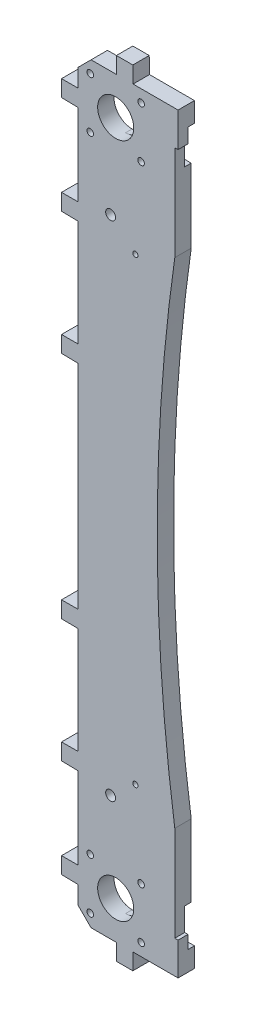
SolidWorks part; units mm, degrees
ref_plane "Front" through (0, 0, 0) normal (0, 0, 1) x (1, 0, 0)
ref_plane "Top" through (0, 0, 0) normal (0, 1, 0) x (1, 0, 0)
ref_plane "Right" through (0, 0, 0) normal (1, 0, 0) x (0, 0, -1)
sketch "Эскиз2" plane through (0, 0, 0) normal (0, 0, 1) x (1, 0, 0)
  line L0 (-25.5007, 139.9) -> (-25.5007, 109.05)
  line L1 (-35.4993, 140.0666) -> (-25.5007, 139.9)
  line L2 (-35.4993, 150.0666) -> (-35.4993, 140.0666)
  line L3 (-25.5007, 150.1) -> (-35.4993, 150.0666)
  line L4 (-25.5007, 176.55) -> (-25.5007, 150.1)
  line L5 (-25.5007, 199.9) -> (-25.5007, 176.55)
  line L6 (-35.4993, 200.0666) -> (-25.5007, 199.9)
  line L7 (-35.4993, 210.0666) -> (-35.4993, 200.0666)
  line L8 (-25.5007, 210.1) -> (-35.4993, 210.0666)
  line L9 (-25.5007, 221) -> (-25.5007, 210.1)
  line L10 (-17.5007, 229) -> (-25.5007, 221)
  line L11 (-2.1007, 229) -> (-17.5007, 229)
  line L12 (-2.0673, 238.9986) -> (-2.1007, 229)
  line L13 (7.9327, 238.9986) -> (-2.0673, 238.9986)
  line L14 (8.0993, 229) -> (7.9327, 238.9986)
  line L15 (35.4993, 229) -> (8.0993, 229)
  line L16 (8.0993, -229) -> (35.4993, -229)
  line L17 (7.9327, -238.9986) -> (8.0993, -229)
  line L18 (-2.0673, -238.9986) -> (7.9327, -238.9986)
  line L19 (-2.1007, -229) -> (-2.0673, -238.9986)
  line L20 (-17.5007, -229) -> (-2.1007, -229)
  line L21 (-25.5007, -221) -> (-17.5007, -229)
  line L22 (-25.5007, -210.1) -> (-25.5007, -221)
  line L23 (-35.4993, -209.9334) -> (-25.5007, -210.1)
  line L24 (-35.4993, -199.9334) -> (-35.4993, -209.9334)
  line L25 (-25.5007, -199.9) -> (-35.4993, -199.9334)
  line L26 (-25.5007, -173.45) -> (-25.5007, -199.9)
  line L27 (-25.5007, -150.1) -> (-25.5007, -173.45)
  line L28 (-35.4993, -149.9334) -> (-25.5007, -150.1)
  line L29 (-35.4993, -139.9334) -> (-35.4993, -149.9334)
  line L30 (-25.5007, -139.9) -> (-35.4993, -139.9334)
  line L31 (-25.5007, -105.95) -> (-25.5007, -139.9)
  line L32 (-25.5007, -75.1) -> (-25.5007, -105.95)
  line L33 (-35.4993, -74.9334) -> (-25.5007, -75.1)
  line L34 (-35.4993, -64.9334) -> (-35.4993, -74.9334)
  line L35 (-25.5007, -64.9) -> (-35.4993, -64.9334)
  line L36 (-25.5007, 64.9) -> (-25.5007, -64.9)
  line L37 (-35.4993, 65.0666) -> (-25.5007, 64.9)
  line L38 (-35.4993, 75.0666) -> (-35.4993, 65.0666)
  line L39 (-25.5007, 75.1) -> (-35.4993, 75.0666)
  line L40 (-25.5007, 109.05) -> (-25.5007, 75.1)
  line L41 (33.4993, 208.1167) -> (33.4993, 150.1167)
  line L42 (33.4993, -209) -> (33.4993, -151)
  line L43 (35.4993, -229) -> (35.4993, -209)
  line L44 (35.4993, -209) -> (33.4993, -209)
  line L45 (35.4993, 229) -> (35.4993, 208.1167)
  line L46 (35.4993, 208.1167) -> (33.4993, 208.1167)
  circle A0 centre (-18.0007, -190.5) radius 2
  circle A1 centre (-18.0007, -221.5) radius 2
  circle A2 centre (-18.0007, 190.5) radius 2
  circle A3 centre (12.9993, 221.5) radius 2
  circle A4 centre (-2.5007, -206) radius 11
  circle A5 centre (-2.5007, 206) radius 11
  circle A6 centre (-18.0007, 221.5) radius 2
  circle A7 centre (12.9993, -221.5) radius 2
  circle A8 centre (12.9993, -190.5) radius 2
  circle A9 centre (12.9993, 190.5) radius 2
  arc A12 (33.4993, 150.1167) -> (33.4993, -151) centre (1086.4428, -0.4417) ccw
  circle A15 centre (-5.6007, -153.2) radius 3
  circle A16 centre (-5.6007, 153.2) radius 3
  circle A17 centre (9.4993, -139.9) radius 1.6
  circle A18 centre (9.4993, 139.9) radius 1.6
  point P27 (0, 0)
  dimension "D1" = 58
  dimension "D2" = 58
  dimension "D3" = 2
extrude "Бобышка-Вытянуть1" add sketch "Эскиз2" along normal blind 10
sketch "Эскиз4" plane through (0, 0, 0) normal (0, 0, 1) x (1, 0, 0)
  line L0 (-2.5007, 217) -> (35.4993, 217)
  line L1 (35.4993, 208.1167) -> (35.4993, 229) construction
  line L2 (35.4993, 217) -> (35.4993, 195)
  line L3 (35.4993, 195) -> (-2.5007, 195)
  line L4 (-2.5007, -217) -> (35.4993, -217)
  line L5 (35.4993, -229) -> (35.4993, -209) construction
  line L6 (35.4993, -217) -> (35.4993, -195)
  line L7 (35.4993, -195) -> (-2.5007, -195)
  arc A0 (-2.5007, 217) -> (-2.5007, 195) centre (-2.5007, 206) ccw
  arc A1 (-2.5007, -195) -> (-2.5007, -217) centre (-2.5007, -206) ccw
extrude "Вырез-Вытянуть2" cut sketch "Эскиз4" along normal blind 4
